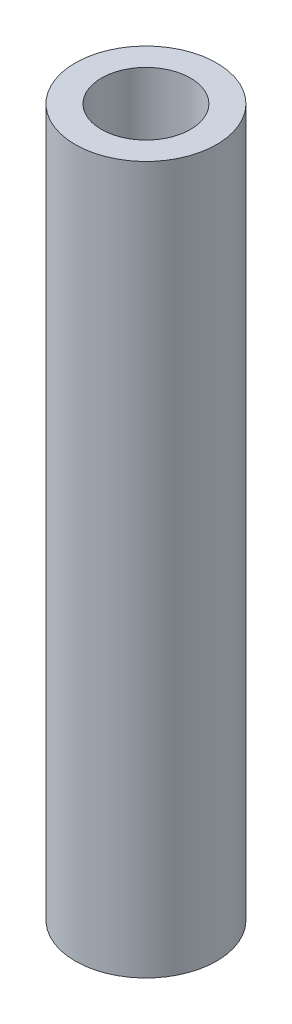
SolidWorks part; units mm, degrees
ref_plane "Front Plane" through (0, 0, 0) normal (0, 0, 1) x (1, 0, 0)
ref_plane "Top Plane" through (0, 0, 0) normal (0, 1, 0) x (1, 0, 0)
ref_plane "Right Plane" through (0, 0, 0) normal (1, 0, 0) x (0, 0, -1)
sketch "Sketch2" plane through (0, 0, 0) normal (0, 1, 0) x (1, 0, 0)
  circle A0 centre (0, 0) radius 3.175
  circle A1 centre (0, 0) radius 2
  dimension "D1" = 4
  dimension "D2" = 6.35
extrude "Boss-Extrude1" add sketch "Sketch2" along normal blind 31.75
